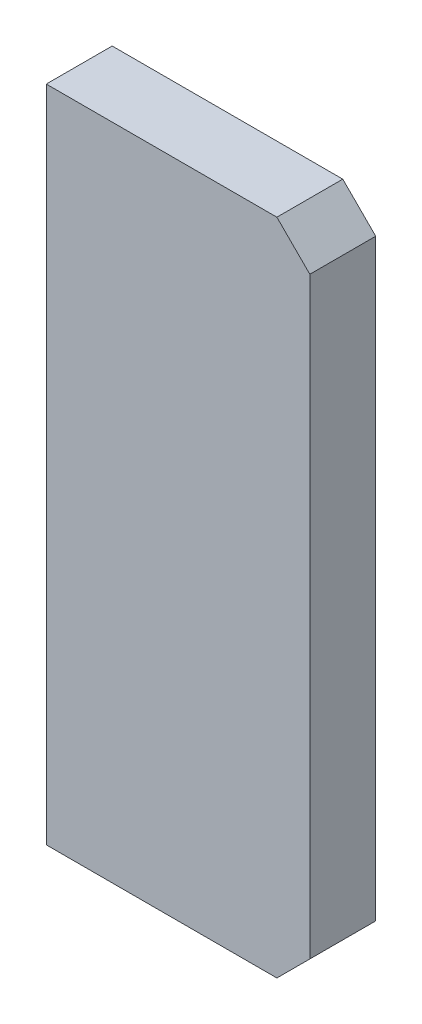
SolidWorks part; units mm, degrees
ref_plane "Front Plane" through (0, 0, 0) normal (1, 0, 0) x (0, 1, 0)
ref_plane "Top Plane" through (0, 0, 0) normal (0, 0, 1) x (0, 1, 0)
ref_plane "Right Plane" through (0, 0, 0) normal (0, 1, 0) x (-1, 0, 0)
sketch "Sketch1" plane through (0, 0, 0) normal (0, 0, 1) x (0, 1, 0)
  line L1 (-500, -200) -> (500, -200)
  line L2 (-500, -200) -> (-500, 200)
  line L3 (-500, 200) -> (500, 200)
  line L4 (500, -200) -> (500, 200)
  line L5 (-500, -200) -> (500, 200) construction
  line L6 (-500, 200) -> (500, -200) construction
  point P0 (0, 0)
  dimension "D1" = 1000
  dimension "D2" = 400
extrude "Boss-Extrude1" add sketch "Sketch1" along normal blind 100
chamfer "Chamfer1" distance 50 angle 45 2 edges at (200, -500, 50) (200, 500, 50)
